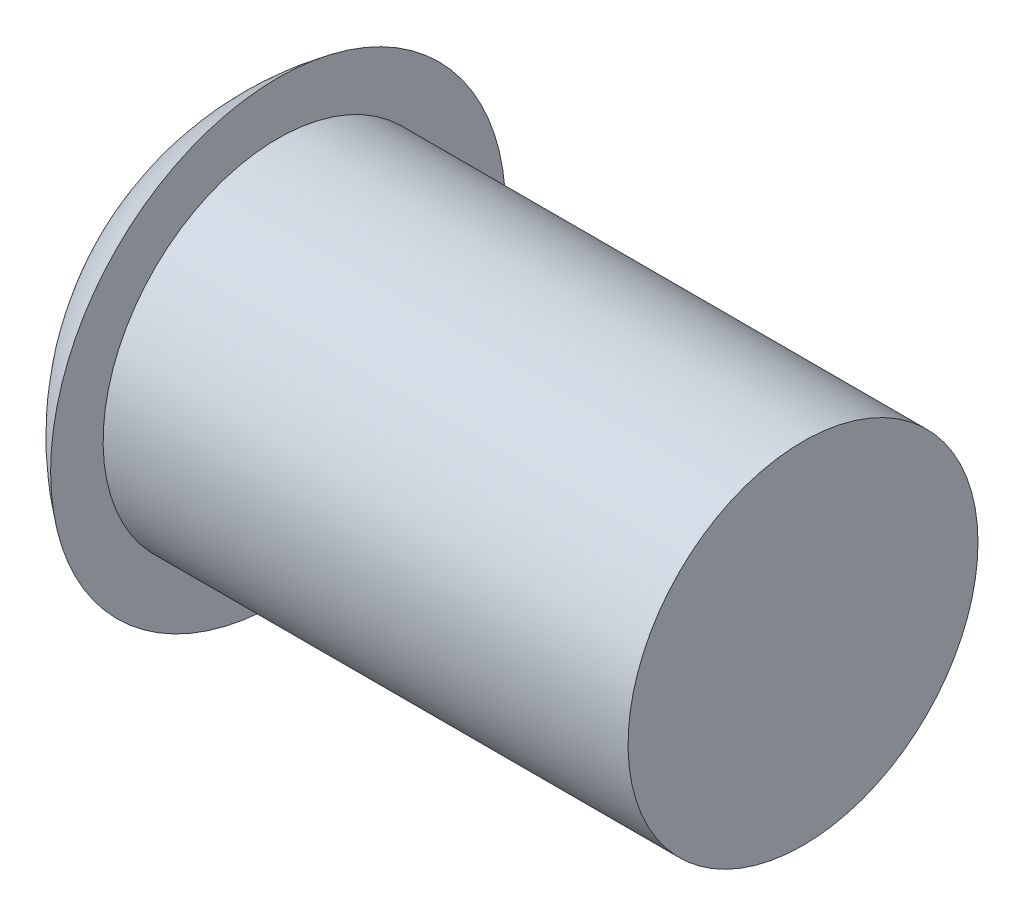
SolidWorks part; units mm, degrees
ref_plane "Front Plane" through (0, 0, 0) normal (0, 0, 1) x (1, 0, 0)
ref_plane "Top Plane" through (0, 0, 0) normal (0, 1, 0) x (1, 0, 0)
ref_plane "Right Plane" through (0, 0, 0) normal (1, 0, 0) x (0, 0, -1)
sketch "Sketch1" plane through (0, 0, 0) normal (1, 0, 0) x (0, 0, -1)
  circle A0 centre (0, 0) radius 5
  dimension "D1" = 10
extrude "Boss-Extrude1" add sketch "Sketch1" along normal blind 15
sketch "Sketch3" plane through (0, 0, 0) normal (0, 0, 1) x (1, 0, 0)
  line L0 (0, 0) -> (-12.2528, 0) construction
  line L1 (0, 0) -> (0, 6.5)
  line L2 (-3.3, 0) -> (-3.3, 7.3908) construction
  line L3 (15, 5) -> (0, 5) construction
  line L4 (-3.3, 0) -> (0, 0)
  arc A0 (-3.3, 0) -> (0, 6.5) centre (4.7515, 0) cw
  dimension "D1" = 1.5
  dimension "D2" = 3.3
revolve "Revolve1" add sketch "Sketch3" angle 360 about L4
